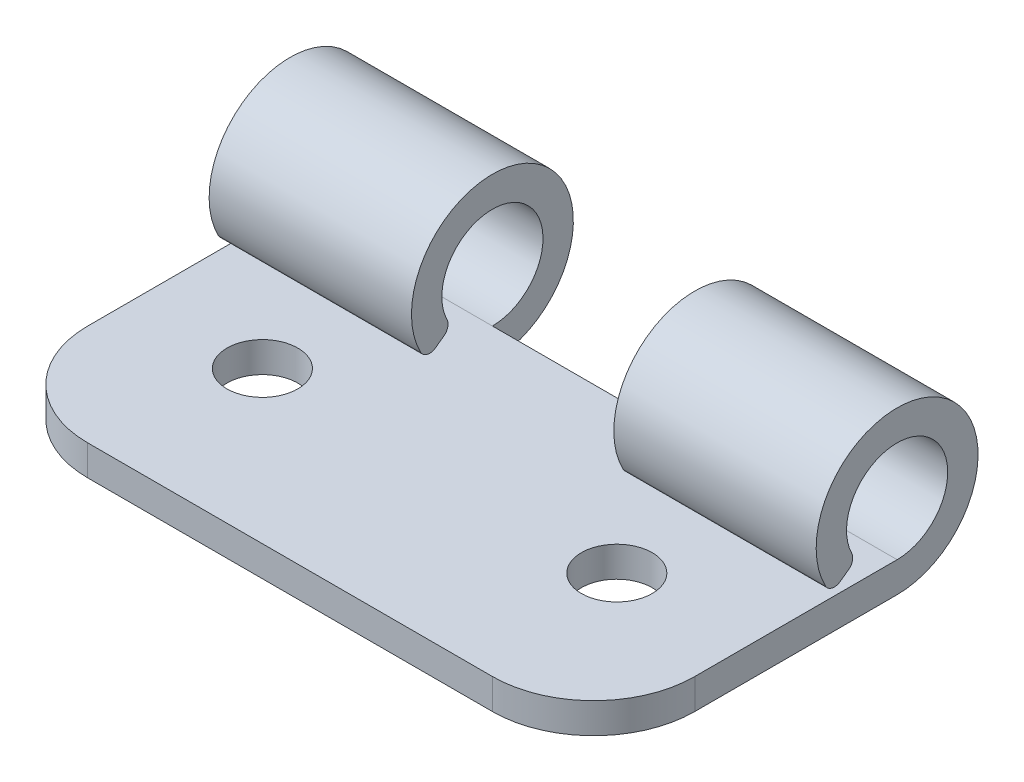
SolidWorks part; units mm, degrees
ref_plane "前视基准面" through (0, 0, 0) normal (0, 0, 1) x (1, 0, 0)
ref_plane "上视基准面" through (0, 0, 0) normal (0, 1, 0) x (1, 0, 0)
ref_plane "右视基准面" through (0, 0, 0) normal (1, 0, 0) x (0, 0, -1)
other "Configuration Table"
sketch "草图1" plane through (0, 0, 0) normal (0, 1, 0) x (1, 0, 0)
  line L1 (-15, -7.5) -> (15, -7.5)
  line L2 (-15, -7.5) -> (-15, 7.5)
  line L3 (-15, 7.5) -> (15, 7.5)
  line L4 (15, -7.5) -> (15, 7.5)
  line L5 (-15, -7.5) -> (15, 7.5) construction
  line L6 (-15, 7.5) -> (15, -7.5) construction
  circle A0 centre (-8.8673, 0) radius 1.75
  circle A1 centre (8.6474, 0) radius 1.75
  point P0 (0, 0)
  dimension "D3" = 3.5
  dimension "D4" = 7.5
  dimension "D5" = 3.5
  dimension "D6" = 7.5
  dimension "D1" = 30
  dimension "D2" = 15
extrude "凸台-拉伸1" add sketch "草图1" along normal blind 1.5 contours A0 | A1 | L3 L4 L1 L2
fillet "圆角1" radius 5 2 edges at (15, 0.75, 7.5) (-15, 0.75, 7.5)
sketch "草图2" plane through (15, 0, 0) normal (1, 0, 0) x (0, 0, -1)
  line L0 (7.5, 0) -> (7.5, 4) construction
  line L1 (7.5, 1.5) -> (7.5, 0)
  line L2 (4.6894, 1.9751) -> (5.1, 2.2709)
  arc A0 (7.5, 0) -> (3.9538, 2.1494) centre (7.5, 4) ccw
  arc A1 (7.5, 1.5) -> (5.2564, 2.8971) centre (7.5, 4) ccw
  arc A2 (4.6894, 1.9751) -> (3.9538, 2.1494) centre (4.3971, 2.3808) cw
  arc A3 (5.2564, 2.8971) -> (5.1, 2.2709) centre (4.8077, 2.6766) cw
  dimension "D2" = 0.5
  dimension "D3" = 2.5
  dimension "D1" = 4
extrude "凸台-拉伸2" add sketch "草图2" against normal blind 10
mirror "镜向1" about plane through (0, 0, 0) normal (1, 0, 0) of "凸台-拉伸2"
